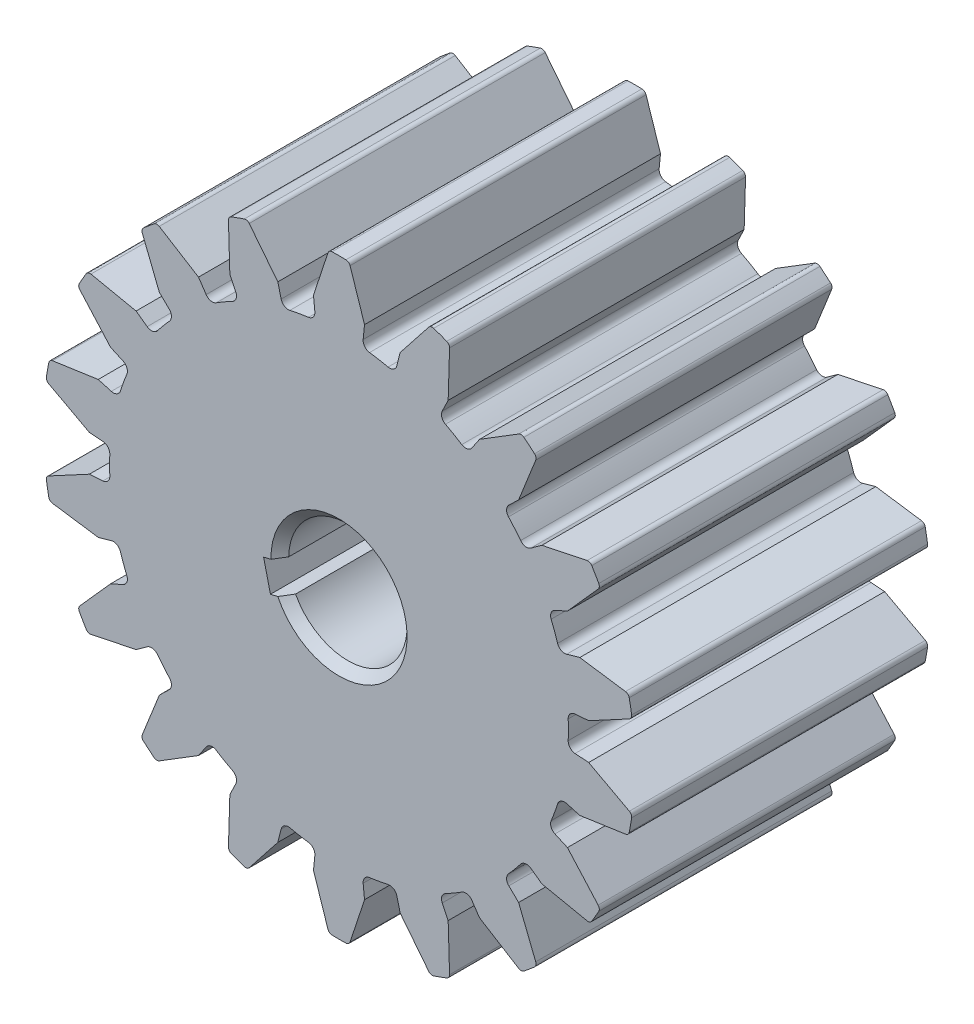
SolidWorks part; units mm, degrees
ref_plane "前视基准面" through (0, 0, 0) normal (0, 0, 1) x (1, 0, 0)
ref_plane "上视基准面" through (0, 0, 0) normal (0, 1, 0) x (1, 0, 0)
ref_plane "右视基准面" through (0, 0, 0) normal (1, 0, 0) x (0, 0, -1)
sketch "草图1" plane through (0, 0, 0) normal (0, 0, 1) x (1, 0, 0)
  line L0 (-19.6178, 2.7001) -> (-16.8702, 1.2229)
  line L1 (-16.8702, 1.2229) -> (-15.9503, 1.1562)
  line L2 (-15.9503, -1.1562) -> (-16.8702, -1.2229)
  line L3 (-16.8702, -1.2229) -> (-19.6178, -2.7001)
  line L4 (-19.3582, -4.1724) -> (-16.2711, -4.6208)
  line L5 (-16.2711, -4.6208) -> (-15.3839, -4.3688)
  line L6 (-14.593, -6.5418) -> (-15.4345, -6.9191)
  line L7 (-15.4345, -6.9191) -> (-17.5112, -9.247)
  line L8 (-16.7637, -10.5416) -> (-13.7094, -9.9072)
  line L9 (-13.7094, -9.9072) -> (-12.9619, -9.367)
  line L10 (-11.4755, -11.1384) -> (-12.1373, -11.7808)
  line L11 (-12.1373, -11.7808) -> (-13.2925, -14.6785)
  line L12 (-12.1473, -15.6394) -> (-9.4942, -13.9986)
  line L13 (-9.4942, -13.9986) -> (-8.9765, -13.2353)
  line L14 (-6.9739, -14.3915) -> (-7.376, -15.2215)
  line L15 (-7.376, -15.2215) -> (-7.4705, -18.3395)
  line L16 (-6.0657, -18.8508) -> (-4.1338, -16.4016)
  line L17 (-4.1338, -16.4016) -> (-3.9084, -15.5072)
  line L18 (-1.6311, -15.9088) -> (-1.7252, -16.8263)
  line L19 (-1.7252, -16.8263) -> (-0.7475, -19.7886)
  line L20 (0.7475, -19.7886) -> (1.7252, -16.8263)
  line L21 (1.7252, -16.8263) -> (1.6311, -15.9088)
  line L22 (3.9084, -15.5072) -> (4.1338, -16.4016)
  line L23 (4.1338, -16.4016) -> (6.0657, -18.8508)
  line L24 (7.4705, -18.3395) -> (7.376, -15.2215)
  line L25 (7.376, -15.2215) -> (6.9739, -14.3915)
  line L26 (8.9765, -13.2353) -> (9.4942, -13.9986)
  line L27 (9.4942, -13.9986) -> (12.1473, -15.6394)
  line L28 (13.2925, -14.6785) -> (12.1373, -11.7808)
  line L29 (12.1373, -11.7808) -> (11.4755, -11.1384)
  line L30 (12.9619, -9.367) -> (13.7094, -9.9072)
  line L31 (13.7094, -9.9072) -> (16.7637, -10.5416)
  line L32 (17.5112, -9.247) -> (15.4345, -6.9191)
  line L33 (15.4345, -6.9191) -> (14.593, -6.5418)
  line L34 (15.3839, -4.3688) -> (16.2711, -4.6208)
  line L35 (16.2711, -4.6208) -> (19.3582, -4.1724)
  line L36 (19.6178, -2.7001) -> (16.8702, -1.2229)
  line L37 (16.8702, -1.2229) -> (15.9503, -1.1562)
  line L38 (15.9503, 1.1562) -> (16.8702, 1.2229)
  line L39 (16.8702, 1.2229) -> (19.6178, 2.7001)
  line L40 (19.3582, 4.1724) -> (16.2711, 4.6208)
  line L41 (16.2711, 4.6208) -> (15.3839, 4.3688)
  line L42 (14.593, 6.5418) -> (15.4345, 6.9191)
  line L43 (15.4345, 6.9191) -> (17.5112, 9.247)
  line L44 (16.7637, 10.5416) -> (13.7094, 9.9072)
  line L45 (13.7094, 9.9072) -> (12.9619, 9.367)
  line L46 (11.4755, 11.1384) -> (12.1373, 11.7808)
  line L47 (12.1373, 11.7808) -> (13.2925, 14.6785)
  line L48 (12.1473, 15.6394) -> (9.4942, 13.9986)
  line L49 (9.4942, 13.9986) -> (8.9765, 13.2353)
  line L50 (6.9739, 14.3915) -> (7.376, 15.2215)
  line L51 (7.376, 15.2215) -> (7.4705, 18.3395)
  line L52 (6.0657, 18.8508) -> (4.1338, 16.4016)
  line L53 (4.1338, 16.4016) -> (3.9084, 15.5072)
  line L54 (1.6311, 15.9088) -> (1.7252, 16.8263)
  line L55 (1.7252, 16.8263) -> (0.7475, 19.7886)
  line L56 (-0.7475, 19.7886) -> (-1.7252, 16.8263)
  line L57 (-1.7252, 16.8263) -> (-1.6311, 15.9088)
  line L58 (-3.9084, 15.5072) -> (-4.1338, 16.4016)
  line L59 (-4.1338, 16.4016) -> (-6.0657, 18.8508)
  line L60 (-7.4705, 18.3395) -> (-7.376, 15.2215)
  line L61 (-7.376, 15.2215) -> (-6.9739, 14.3915)
  line L62 (-8.9765, 13.2353) -> (-9.4942, 13.9986)
  line L63 (-9.4942, 13.9986) -> (-12.1473, 15.6394)
  line L64 (-13.2925, 14.6785) -> (-12.1373, 11.7808)
  line L65 (-12.1373, 11.7808) -> (-11.4755, 11.1384)
  line L66 (-12.9619, 9.367) -> (-13.7094, 9.9072)
  line L67 (-13.7094, 9.9072) -> (-16.7637, 10.5416)
  line L68 (-17.5112, 9.247) -> (-15.4345, 6.9191)
  line L69 (-15.4345, 6.9191) -> (-14.593, 6.5418)
  line L70 (-15.3839, 4.3688) -> (-16.2711, 4.6208)
  line L71 (-16.2711, 4.6208) -> (-19.3582, 4.1724)
  arc A0 (-19.7723, 3.0095) -> (-19.6178, 2.7001) centre (-19.4757, 2.9644) ccw
  arc A1 (-15.9503, 1.1562) -> (-15.4869, 0.637) centre (-15.9865, 0.6575) cw
  arc A2 (-15.4869, 0.637) -> (-15.4869, -0.637) centre (0, 0) ccw
  arc A3 (-15.4869, -0.637) -> (-15.9503, -1.1562) centre (-15.9865, -0.6575) cw
  arc A4 (-19.6178, -2.7001) -> (-19.7723, -3.0095) centre (-19.4757, -2.9644) ccw
  arc A5 (-19.7723, -3.0095) -> (-19.6092, -3.9345) centre (0, 0) ccw
  arc A6 (-19.6092, -3.9345) -> (-19.3582, -4.1724) centre (-19.315, -3.8755) ccw
  arc A7 (-15.3839, -4.3688) -> (-14.7708, -4.6983) centre (-15.2473, -4.8498) cw
  arc A8 (-14.7708, -4.6983) -> (-14.3351, -5.8954) centre (0, 0) ccw
  arc A9 (-14.3351, -5.8954) -> (-14.593, -6.5418) centre (-14.7975, -6.0856) cw
  arc A10 (-17.5112, -9.247) -> (-17.5505, -9.5905) centre (-17.2873, -9.4467) ccw
  arc A11 (-17.5505, -9.5905) -> (-17.0809, -10.404) centre (0, 0) ccw
  arc A12 (-17.0809, -10.404) -> (-16.7637, -10.5416) centre (-16.8247, -10.2479) ccw
  arc A13 (-12.9619, -9.367) -> (-12.2731, -9.4668) centre (-12.669, -9.7722) cw
  arc A14 (-12.2731, -9.4668) -> (-11.4542, -10.4427) centre (0, 0) ccw
  arc A15 (-11.4542, -10.4427) -> (-11.4755, -11.1384) centre (-11.8237, -10.7796) cw
  arc A16 (-13.2925, -14.6785) -> (-13.212, -15.0148) centre (-13.0138, -14.7896) ccw
  arc A17 (-13.212, -15.0148) -> (-12.4924, -15.6185) centre (0, 0) ccw
  arc A18 (-12.4924, -15.6185) -> (-12.1473, -15.6394) centre (-12.3051, -15.3843) ccw
  arc A19 (-8.9765, -13.2353) -> (-8.2951, -13.0936) centre (-8.5627, -13.5159) cw
  arc A20 (-8.2951, -13.0936) -> (-7.1918, -13.7305) centre (0, 0) ccw
  arc A21 (-7.1918, -13.7305) -> (-6.9739, -14.3915) centre (-7.4238, -14.1735) cw
  arc A22 (-7.4705, -18.3395) -> (-7.2798, -18.628) centre (-7.1706, -18.3486) ccw
  arc A23 (-7.2798, -18.628) -> (-6.3972, -18.9493) centre (0, 0) ccw
  arc A24 (-6.3972, -18.9493) -> (-6.0657, -18.8508) centre (-6.3013, -18.6651) ccw
  arc A25 (-3.9084, -15.5072) -> (-3.3166, -15.141) centre (-3.4236, -15.6294) cw
  arc A26 (-3.3166, -15.141) -> (-2.062, -15.3622) centre (0, 0) ccw
  arc A27 (-2.062, -15.3622) -> (-1.6311, -15.9088) centre (-2.1285, -15.8578) cw
  arc A28 (-0.7475, -19.7886) -> (-0.4696, -19.9945) centre (-0.4626, -19.6946) ccw
  arc A29 (-0.4696, -19.9945) -> (0.4696, -19.9945) centre (0, 0) ccw
  arc A30 (0.4696, -19.9945) -> (0.7475, -19.7886) centre (0.4626, -19.6946) ccw
  arc A31 (1.6311, -15.9088) -> (2.062, -15.3622) centre (2.1285, -15.8578) cw
  arc A32 (2.062, -15.3622) -> (3.3166, -15.141) centre (0, 0) ccw
  arc A33 (3.3166, -15.141) -> (3.9084, -15.5072) centre (3.4236, -15.6294) cw
  arc A34 (6.0657, -18.8508) -> (6.3972, -18.9493) centre (6.3013, -18.6651) ccw
  arc A35 (6.3972, -18.9493) -> (7.2798, -18.628) centre (0, 0) ccw
  arc A36 (7.2798, -18.628) -> (7.4705, -18.3395) centre (7.1706, -18.3486) ccw
  arc A37 (6.9739, -14.3915) -> (7.1918, -13.7305) centre (7.4238, -14.1735) cw
  arc A38 (7.1918, -13.7305) -> (8.2951, -13.0936) centre (0, 0) ccw
  arc A39 (8.2951, -13.0936) -> (8.9765, -13.2353) centre (8.5627, -13.5159) cw
  arc A40 (12.1473, -15.6394) -> (12.4924, -15.6185) centre (12.3051, -15.3843) ccw
  arc A41 (12.4924, -15.6185) -> (13.212, -15.0148) centre (0, 0) ccw
  arc A42 (13.212, -15.0148) -> (13.2925, -14.6785) centre (13.0138, -14.7896) ccw
  arc A43 (11.4755, -11.1384) -> (11.4542, -10.4427) centre (11.8237, -10.7796) cw
  arc A44 (11.4542, -10.4427) -> (12.2731, -9.4668) centre (0, 0) ccw
  arc A45 (12.2731, -9.4668) -> (12.9619, -9.367) centre (12.669, -9.7722) cw
  arc A46 (16.7637, -10.5416) -> (17.0809, -10.404) centre (16.8247, -10.2479) ccw
  arc A47 (17.0809, -10.404) -> (17.5505, -9.5905) centre (0, 0) ccw
  arc A48 (17.5505, -9.5905) -> (17.5112, -9.247) centre (17.2873, -9.4467) ccw
  arc A49 (14.593, -6.5418) -> (14.3351, -5.8954) centre (14.7975, -6.0856) cw
  arc A50 (14.3351, -5.8954) -> (14.7708, -4.6983) centre (0, 0) ccw
  arc A51 (14.7708, -4.6983) -> (15.3839, -4.3688) centre (15.2473, -4.8498) cw
  arc A52 (19.3582, -4.1724) -> (19.6092, -3.9345) centre (19.315, -3.8755) ccw
  arc A53 (19.6092, -3.9345) -> (19.7723, -3.0095) centre (0, 0) ccw
  arc A54 (19.7723, -3.0095) -> (19.6178, -2.7001) centre (19.4757, -2.9644) ccw
  arc A55 (15.9503, -1.1562) -> (15.4869, -0.637) centre (15.9865, -0.6575) cw
  arc A56 (15.4869, -0.637) -> (15.4869, 0.637) centre (0, 0) ccw
  arc A57 (15.4869, 0.637) -> (15.9503, 1.1562) centre (15.9865, 0.6575) cw
  arc A58 (19.6178, 2.7001) -> (19.7723, 3.0095) centre (19.4757, 2.9644) ccw
  arc A59 (19.7723, 3.0095) -> (19.6092, 3.9345) centre (0, 0) ccw
  arc A60 (19.6092, 3.9345) -> (19.3582, 4.1724) centre (19.315, 3.8755) ccw
  arc A61 (15.3839, 4.3688) -> (14.7708, 4.6983) centre (15.2473, 4.8498) cw
  arc A62 (14.7708, 4.6983) -> (14.3351, 5.8954) centre (0, 0) ccw
  arc A63 (14.3351, 5.8954) -> (14.593, 6.5418) centre (14.7975, 6.0856) cw
  arc A64 (17.5112, 9.247) -> (17.5505, 9.5905) centre (17.2873, 9.4467) ccw
  arc A65 (17.5505, 9.5905) -> (17.0809, 10.404) centre (0, 0) ccw
  arc A66 (17.0809, 10.404) -> (16.7637, 10.5416) centre (16.8247, 10.2479) ccw
  arc A67 (12.9619, 9.367) -> (12.2731, 9.4668) centre (12.669, 9.7722) cw
  arc A68 (12.2731, 9.4668) -> (11.4542, 10.4427) centre (0, 0) ccw
  arc A69 (11.4542, 10.4427) -> (11.4755, 11.1384) centre (11.8237, 10.7796) cw
  arc A70 (13.2925, 14.6785) -> (13.212, 15.0148) centre (13.0138, 14.7896) ccw
  arc A71 (13.212, 15.0148) -> (12.4924, 15.6185) centre (0, 0) ccw
  arc A72 (12.4924, 15.6185) -> (12.1473, 15.6394) centre (12.3051, 15.3843) ccw
  arc A73 (8.9765, 13.2353) -> (8.2951, 13.0936) centre (8.5627, 13.5159) cw
  arc A74 (8.2951, 13.0936) -> (7.1918, 13.7305) centre (0, 0) ccw
  arc A75 (7.1918, 13.7305) -> (6.9739, 14.3915) centre (7.4238, 14.1735) cw
  arc A76 (7.4705, 18.3395) -> (7.2798, 18.628) centre (7.1706, 18.3486) ccw
  arc A77 (7.2798, 18.628) -> (6.3972, 18.9493) centre (0, 0) ccw
  arc A78 (6.3972, 18.9493) -> (6.0657, 18.8508) centre (6.3013, 18.6651) ccw
  arc A79 (3.9084, 15.5072) -> (3.3166, 15.141) centre (3.4236, 15.6294) cw
  arc A80 (3.3166, 15.141) -> (2.062, 15.3622) centre (0, 0) ccw
  arc A81 (2.062, 15.3622) -> (1.6311, 15.9088) centre (2.1285, 15.8578) cw
  arc A82 (0.7475, 19.7886) -> (0.4696, 19.9945) centre (0.4626, 19.6946) ccw
  arc A83 (0.4696, 19.9945) -> (-0.4696, 19.9945) centre (0, 0) ccw
  arc A84 (-0.4696, 19.9945) -> (-0.7475, 19.7886) centre (-0.4626, 19.6946) ccw
  arc A85 (-1.6311, 15.9088) -> (-2.062, 15.3622) centre (-2.1285, 15.8578) cw
  arc A86 (-2.062, 15.3622) -> (-3.3166, 15.141) centre (0, 0) ccw
  arc A87 (-3.3166, 15.141) -> (-3.9084, 15.5072) centre (-3.4236, 15.6294) cw
  arc A88 (-6.0657, 18.8508) -> (-6.3972, 18.9493) centre (-6.3013, 18.6651) ccw
  arc A89 (-6.3972, 18.9493) -> (-7.2798, 18.628) centre (0, 0) ccw
  arc A90 (-7.2798, 18.628) -> (-7.4705, 18.3395) centre (-7.1706, 18.3486) ccw
  arc A91 (-6.9739, 14.3915) -> (-7.1918, 13.7305) centre (-7.4238, 14.1735) cw
  arc A92 (-7.1918, 13.7305) -> (-8.2951, 13.0936) centre (0, 0) ccw
  arc A93 (-8.2951, 13.0936) -> (-8.9765, 13.2353) centre (-8.5627, 13.5159) cw
  arc A94 (-12.1473, 15.6394) -> (-12.4924, 15.6185) centre (-12.3051, 15.3843) ccw
  arc A95 (-12.4924, 15.6185) -> (-13.212, 15.0148) centre (0, 0) ccw
  arc A96 (-13.212, 15.0148) -> (-13.2925, 14.6785) centre (-13.0138, 14.7896) ccw
  arc A97 (-11.4755, 11.1384) -> (-11.4542, 10.4427) centre (-11.8237, 10.7796) cw
  arc A98 (-11.4542, 10.4427) -> (-12.2731, 9.4668) centre (0, 0) ccw
  arc A99 (-12.2731, 9.4668) -> (-12.9619, 9.367) centre (-12.669, 9.7722) cw
  arc A100 (-16.7637, 10.5416) -> (-17.0809, 10.404) centre (-16.8247, 10.2479) ccw
  arc A101 (-17.0809, 10.404) -> (-17.5505, 9.5905) centre (0, 0) ccw
  arc A102 (-17.5505, 9.5905) -> (-17.5112, 9.247) centre (-17.2873, 9.4467) ccw
  arc A103 (-14.593, 6.5418) -> (-14.3351, 5.8954) centre (-14.7975, 6.0856) cw
  arc A104 (-14.3351, 5.8954) -> (-14.7708, 4.6983) centre (0, 0) ccw
  arc A105 (-14.7708, 4.6983) -> (-15.3839, 4.3688) centre (-15.2473, 4.8498) cw
  arc A106 (-19.3582, 4.1724) -> (-19.6092, 3.9345) centre (-19.315, 3.8755) ccw
  arc A107 (-19.6092, 3.9345) -> (-19.7723, 3.0095) centre (0, 0) ccw
extrude "凸台-拉伸1" add sketch "草图1" against normal blind 20
sketch "草图2" plane through (0, 0, 0) normal (1, 0, 0) x (0, 0, -1)
  line L0 (0, 0) -> (0, 4.6)
  line L1 (0, 4.6) -> (0.6, 4)
  line L2 (0.6, 4) -> (19.4, 4)
  line L3 (19.4, 4) -> (20, 4.6)
  line L4 (20, 4.6) -> (20, 0)
  line L5 (20, 0) -> (0, 0)
  line L6 (20, 0) -> (0, 0) construction
revolve "切除-旋转1" cut sketch "草图2" angle 360 about L6
other "冻结***"
sketch "草图4" plane through (0, 0, -20) normal (0, 0, -1) x (-1, 0, 0)
  line L1 (5.0956, -0.1856) -> (4.6323, -2.1312)
  line L2 (4.6323, -2.1312) -> (-0.2317, -0.9728)
  line L3 (5.0956, -0.1856) -> (0.2317, 0.9728)
  line L4 (0.2317, 0.9728) -> (-0.2317, -0.9728)
extrude "切除-拉伸1" cut sketch "草图4" against normal through all
sketch "草图5" plane through (0, 0, -20) normal (0, 0, -1) x (-1, 0, 0)
  circle A0 centre (0, 0) radius 18
sketch "草图6" plane through (0, 0, 0) normal (0, 0, 1) x (1, 0, 0)
  circle A0 centre (0, 0) radius 18
